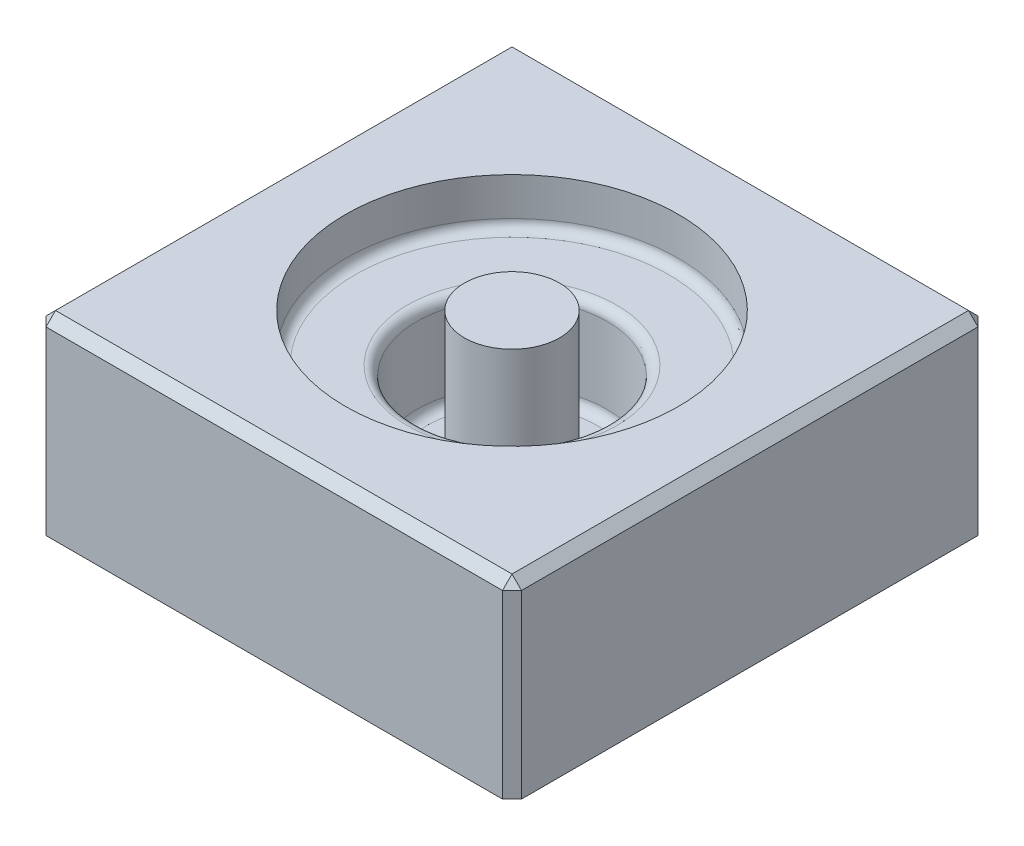
SolidWorks part; units mm, degrees
ref_plane "Front Plane" through (0, 0, 0) normal (0, 0, 1) x (1, 0, 0)
ref_plane "Top Plane" through (0, 0, 0) normal (0, 1, 0) x (1, 0, 0)
ref_plane "Right Plane" through (0, 0, 0) normal (1, 0, 0) x (0, 0, -1)
sketch "Sketch1" plane through (0, 0, 0) normal (0, 1, 0) x (1, 0, 0)
  line L1 (-31.75, 31.75) -> (31.75, 31.75)
  line L2 (-31.75, 31.75) -> (-31.75, -31.75)
  line L3 (-31.75, -31.75) -> (31.75, -31.75)
  line L4 (31.75, 31.75) -> (31.75, -31.75)
  line L5 (-31.75, 31.75) -> (31.75, -31.75) construction
  line L6 (-31.75, -31.75) -> (31.75, 31.75) construction
  point P0 (0, 0)
  dimension "D1" = 63.5
  dimension "D2" = 63.5
extrude "Boss-Extrude1" add sketch "Sketch1" along normal blind 25.4
sketch "Sketch2" plane through (0, 25.4, 0) normal (0, 1, 0) x (1, 0, 0)
  circle A0 centre (0, 0) radius 22.225
  dimension "D1" = 44.45
extrude "Cut-Extrude1" cut sketch "Sketch2" against normal blind 6.35 contours A0
sketch "Sketch3" plane through (0, 19.05, 0) normal (0, 1, 0) x (1, 0, 0)
  circle A0 centre (0, 0) radius 12.7
  dimension "D1" = 25.4
extrude "Cut-Extrude2" cut sketch "Sketch3" against normal blind 12.7
sketch "Sketch4" plane through (0, 6.35, 0) normal (0, 1, 0) x (1, 0, 0)
  circle A0 centre (0, 0) radius 6.35
  dimension "D1" = 12.7
extrude "Boss-Extrude2" add sketch "Sketch4" along normal up to surface (19.05 mm away) up to face at (0, 25.4, 22.225)
fillet "Fillet1" radius 1.27 4 edges at (0, 19.05, 22.225) (0, 19.05, 12.7) (0, 6.35, 12.7) (0, 6.35, 6.35)
chamfer "Chamfer1" distance 1.27 angle 45 8 edges at (-31.75, 12.7, 31.75) (-31.75, 12.7, -31.75) (31.75, 12.7, -31.75) (31.75, 12.7, 31.75) (0, 25.4, -31.75) (31.75, 25.4, 0) (-31.75, 25.4, 0) (0, 25.4, 31.75)
